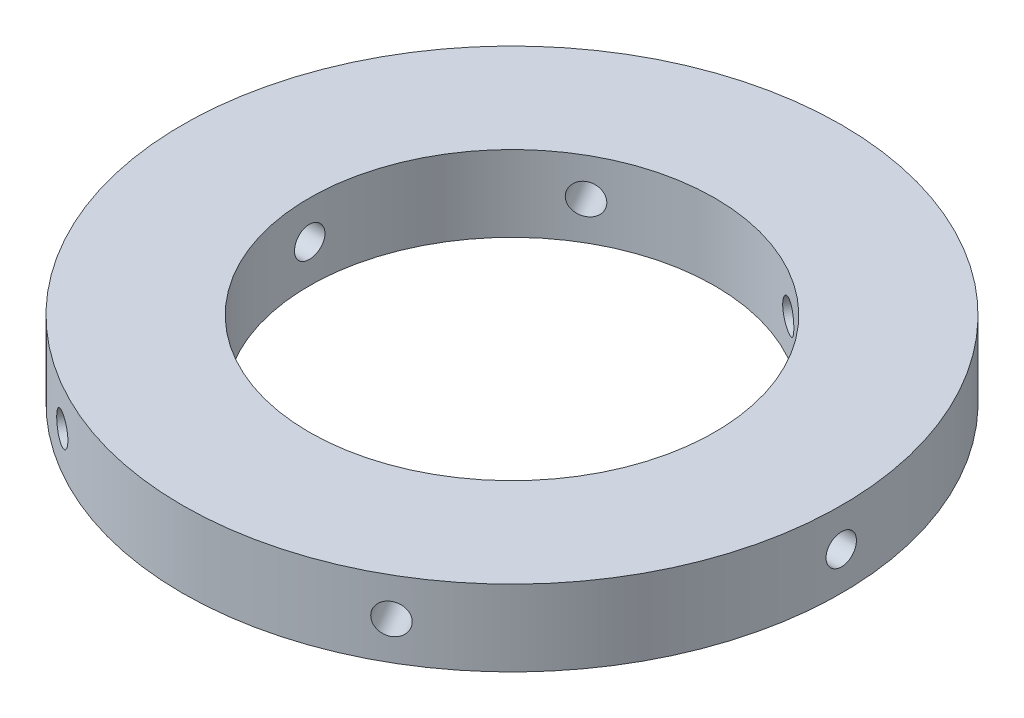
SolidWorks part; units mm, degrees
ref_plane "Front Plane" through (0, 0, 0) normal (0, 0, 1) x (1, 0, 0)
ref_plane "Top Plane" through (0, 0, 0) normal (0, 1, 0) x (1, 0, 0)
ref_plane "Right Plane" through (0, 0, 0) normal (1, 0, 0) x (0, 0, -1)
sketch "Sketch1" plane through (0, 0, 0) normal (0, 1, 0) x (1, 0, 0)
  line L0 (0, 0) -> (0, 87.698) construction
  line L1 (0, 0) -> (-128.1213, 0) construction
  circle A0 centre (0, 0) radius 65
  circle A1 centre (0, 0) radius 40
  dimension "D1" = 130
  dimension "D2" = 80
extrude "Boss-Extrude1" add sketch "Sketch1" along normal blind 15
sketch "Sketch2" plane through (0, 0, 0) normal (1, 0, 0) x (0, 0, -1)
  line L0 (65, 7.5) -> (-65, 7.5) construction
  line L1 (65, 0) -> (65, 15) construction
  line L2 (-65, 15) -> (-65, 0) construction
  circle A0 centre (0, 7.5) radius 3
  dimension "D1" = 6
extrude "Cut-Extrude1" cut sketch "Sketch2" against normal through all
pattern_circular "CirPattern1" count 6 over 360 about axis through (0, 15, 0) along (0, 1, 0) of "Cut-Extrude1"
equation "\"holes\"=6"
equation "\"D1@CirPattern1\"=\"holes\""
